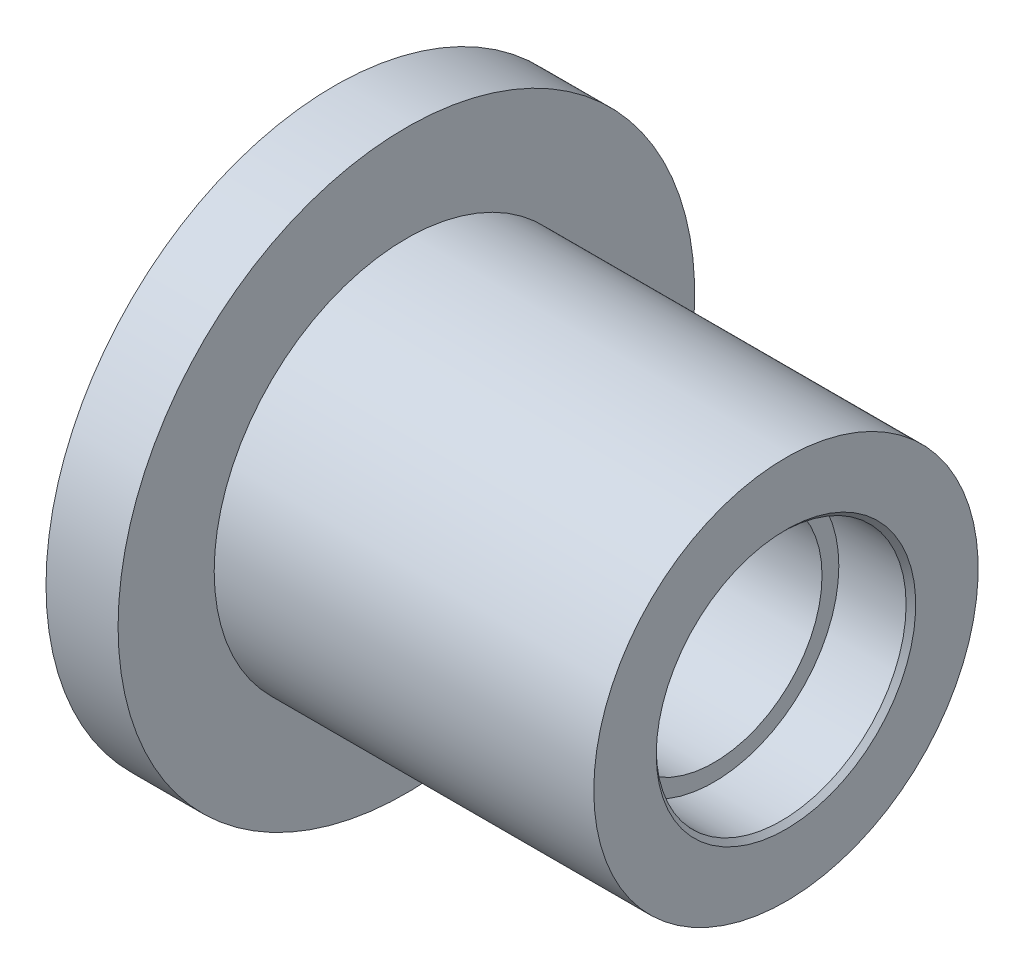
SolidWorks part; units mm, degrees
ref_plane "Front Plane" through (0, 0, 0) normal (0, 0, 1) x (1, 0, 0)
ref_plane "Top Plane" through (0, 0, 0) normal (0, 1, 0) x (1, 0, 0)
ref_plane "Right Plane" through (0, 0, 0) normal (1, 0, 0) x (0, 0, -1)
sketch "Sketch1" plane through (0, 0, 0) normal (0, 0, 1) x (1, 0, 0)
  line L0 (0, 0) -> (100, 0) construction
  line L1 (0, 0) -> (0, 40)
  line L2 (0, 40) -> (6, 40)
  line L3 (6, 40) -> (6, 60)
  line L4 (6, 60) -> (21, 60)
  line L5 (21, 60) -> (21, 40)
  line L6 (21, 40) -> (100, 40)
  line L7 (100, 40) -> (100, 0)
  line L8 (0, 0) -> (100, 0)
  dimension "D1" = 100
  dimension "D2" = 15
  dimension "D3" = 6
  dimension "D4" = 40
  dimension "D5" = 60
  dimension "D6" = 40
revolve "Revolve1" add sketch "Sketch1" angle 360 about L0
ref_plane "Plane1" through (0, 0, -40) normal (0, 0, -1) x (-1, 0, 0)
sketch "Sketch2" plane through (0, 0, -40) normal (0, 0, -1) x (-1, 0, 0)
  line L0 (-100, 0) -> (0, 0) construction
  line L1 (-100, 40) -> (-100, -40) construction
  line L3 (-70, 12.49) -> (-50, 12.49)
  line L4 (-70, 12.49) -> (-70, -12.49)
  line L5 (-70, -12.49) -> (-50, -12.49)
  line L6 (-50, 12.49) -> (-50, -12.49)
  line L7 (-70, 12.49) -> (-50, -12.49) construction
  line L8 (-70, -12.49) -> (-50, 12.49) construction
  point P5 (-60, 0)
  dimension "D1" = 24.98
  dimension "D2" = 20
  dimension "D3" = 30
extrude "Cut-Extrude1" cut sketch "Sketch2" against normal blind 3
hole_wizard "CBORE for M5 Hex Socket Head Cap Screw1" positions "Sketch4" profile "Sketch6" counterbore size "M5" standard "ISO" end condition through all
sketch "Sketch4" plane through (100, 0, 0) normal (1, 0, 0) x (0, 0, -1)
  point P0 (0, 0)
sketch "Sketch6" plane through (100, 0, 0) normal (0, 1, 0) x (0, 0, -1)
  line L0 (0, 0) -> (0, 100)
  line L1 (0, 100) -> (22.5, 100)
  line L3 (22.5, 100) -> (22.5, 15)
  line L4 (22.5, 15) -> (26, 15)
  line L5 (26, 15) -> (26, 0)
  line L7 (26, 0) -> (0, 0)
  line L11 (0, -6.35) -> (0, 107.95) construction
  dimension "Thru Hole Dia." = 45
  dimension "Thru Hole Depth" = 100
  dimension "C'Bore Dia." = 52
  dimension "C'Bore Depth" = 15
chamfer "Chamfer1" distance 1 angle 45 1 edges at (100, 0, -26)
sketch "Sketch11" [suppressed] plane through (0, 0, 0) normal (-1, 0, 0) x (0, 0, 1)
  circle A0 centre (0, 0) radius 50 construction
  dimension "D1" = 100
hole_wizard "CBORE for M6 Hex Socket Head Cap Screw1" [suppressed] positions "Sketch12" profile "Sketch13" counterbore size "M6" standard "ISO"
sketch "Sketch12" [suppressed] plane through (21, 0, 0) normal (1, 0, 0) x (0, 0, -1)
  circle A0 centre (0, 0) radius 50 construction
  point P0 (0, 50)
  point P4 (-50, 0)
  point P6 (0, -50)
  point P8 (50, 0)
sketch "Sketch13" plane through (21, 50, 0) normal (0, 1, 0) x (0, 0, -1)
  line L0 (0, 0) -> (0, 21)
  line L1 (0, 21) -> (4.5, 21)
  line L3 (4.5, 21) -> (4.5, 8)
  line L4 (4.5, 8) -> (7.5, 8)
  line L5 (7.5, 8) -> (7.5, 0)
  line L7 (7.5, 0) -> (0, 0)
  line L11 (0, -6.35) -> (0, 107.95) construction
  dimension "Thru Hole Dia." = 9
  dimension "Thru Hole Depth" = 21
  dimension "C'Bore Dia." = 15
  dimension "C'Bore Depth" = 8
sketch "Sketch15" plane through (0, 0, 0) normal (-1, 0, 0) x (0, 0, 1)
  circle A0 centre (0, 0) radius 26
  dimension "D1" = 52
extrude "Cut-Extrude2" cut sketch "Sketch15" against normal blind 29
sketch "Sketch16" plane through (0, 0, 0) normal (0, 0, 1) x (1, 0, 0)
  line L0 (0, 0) -> (100, 0) construction
  line L1 (100, -40) -> (100, 40) construction
  line L2 (11.85, 0) -> (11.85, 27.5)
  line L3 (11.85, 27.5) -> (14, 27.5)
  line L4 (14, 27.5) -> (14, 0)
  line L5 (11.85, 0) -> (14, 0)
  dimension "D1" = 2.15
  dimension "D2" = 27.5
  dimension "D3" = 11.85
revolve "Cut-Revolve1" cut sketch "Sketch16" angle 360 about L0
